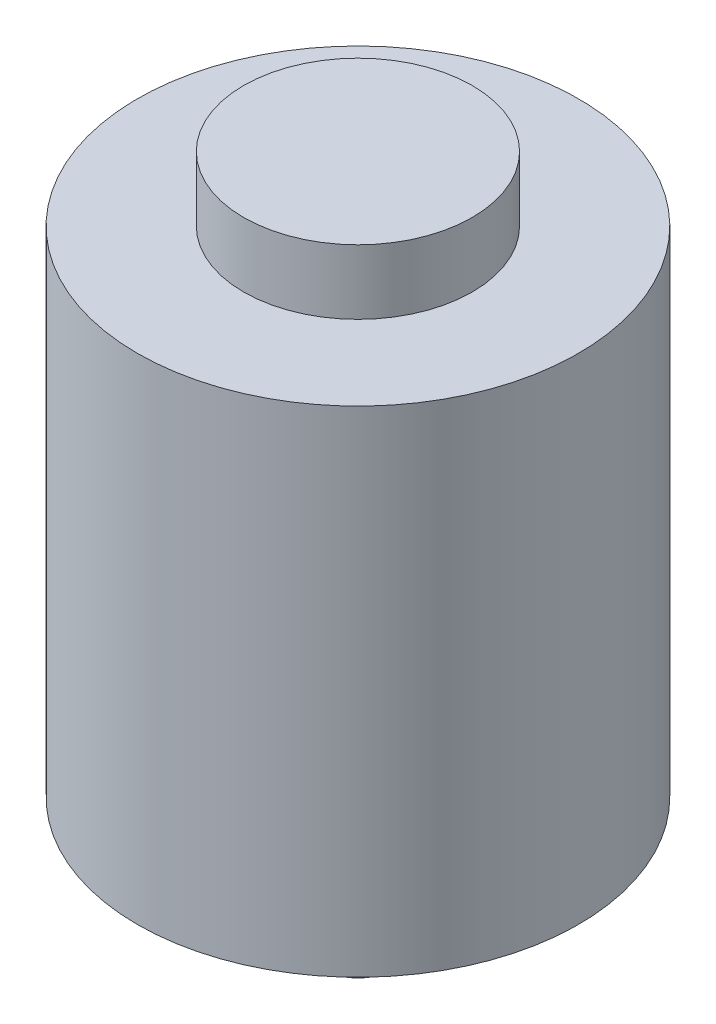
SolidWorks part; units mm, degrees
ref_plane "Plano frontal" through (0, 0, 0) normal (0, 0, 1) x (1, 0, 0)
ref_plane "Plano superior" through (0, 0, 0) normal (0, 1, 0) x (1, 0, 0)
ref_plane "Plano direito" through (0, 0, 0) normal (1, 0, 0) x (0, 0, -1)
sketch "Esboço1" plane through (0, 0, 0) normal (0, 1, 0) x (1, 0, 0)
  circle A0 centre (0, 0) radius 17.075
  dimension "D1" = 34.15
extrude "Ressalto-extrusão1" add sketch "Esboço1" along normal blind 38.3
sketch "Esboço2" plane through (0, 38.3, 0) normal (0, 1, 0) x (1, 0, 0)
  circle A0 centre (0, 0) radius 8.85
  dimension "D1" = 17.7
extrude "Ressalto-extrusão2" add sketch "Esboço2" along normal blind 5
sketch "Esboço3" plane through (0, 0, 0) normal (0, -1, 0) x (1, 0, 0)
  circle A0 centre (0, 0) radius 4
  dimension "D1" = 8
extrude "Ressalto-extrusão3" add sketch "Esboço3" along normal blind 3
sketch "Esboço5" plane through (0, -3, 0) normal (0, -1, 0) x (1, 0, 0)
  circle A0 centre (0, 0) radius 1
  dimension "D1" = 2
extrude "Ressalto-extrusão4" add sketch "Esboço5" along normal blind 7
sketch "Esboço6" plane through (0, -10, 0) normal (0, -1, 0) x (1, 0, 0)
  circle A0 centre (0, 0) radius 3
  dimension "D1" = 6
extrude "Ressalto-extrusão5" add sketch "Esboço6" against normal blind 4
